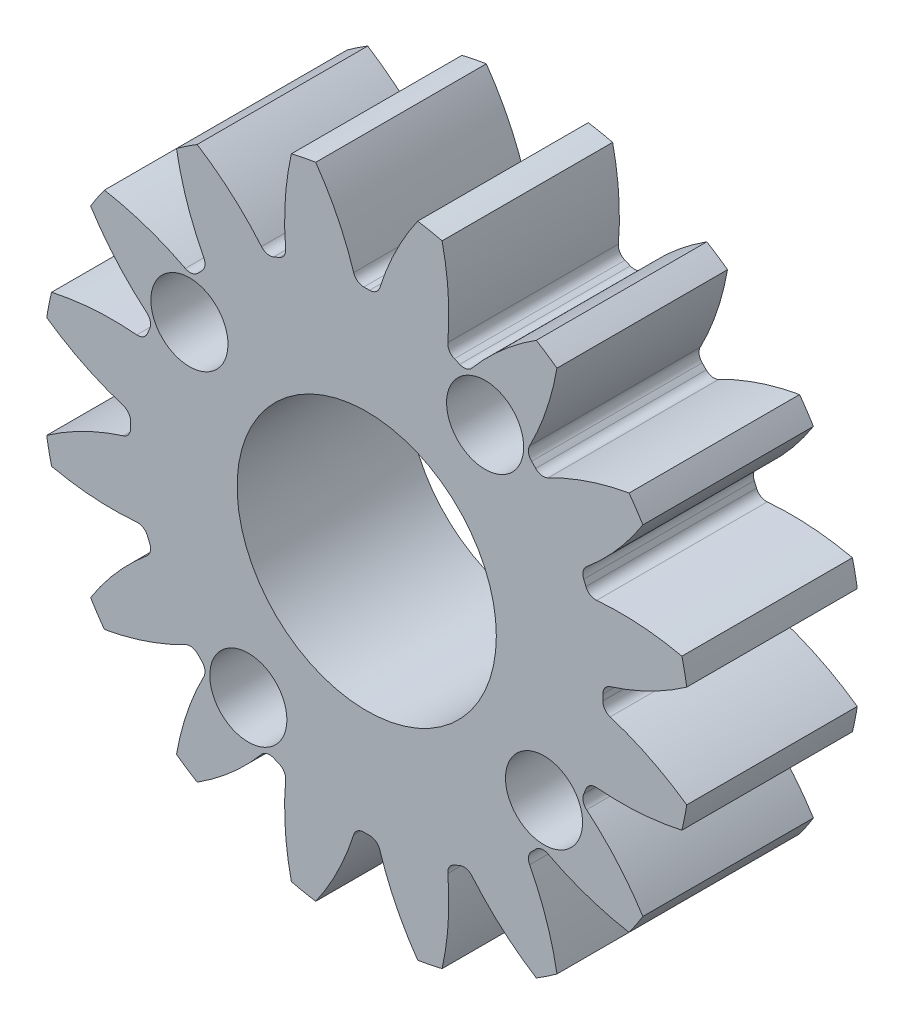
SolidWorks part; units mm, degrees
ref_plane "Front Plane" through (0, 0, 0) normal (0, 0, 1) x (1, 0, 0)
ref_plane "Top Plane" through (0, 0, 0) normal (0, 1, 0) x (1, 0, 0)
ref_plane "Right Plane" through (0, 0, 0) normal (1, 0, 0) x (0, 0, -1)
sketch "Sketch1" plane through (0, 0, 0) normal (0, 0, 1) x (1, 0, 0)
  line L0 (-203.2, 0) -> (203.2, 0) construction
  circle A0 centre (0, 0) radius 12.065 construction
  circle A1 centre (0, 0) radius 10.4775 construction
  circle A2 centre (0, 0) radius 8.7908 construction
  circle A3 centre (0, 0) radius 10.3251 construction
  circle A4 centre (0, 0) radius 6.35 construction
  circle A5 centre (0, 0) radius 10.3187 construction
  dimension "D2" = 1.5875
  dimension "D3" = 3.2742
  dimension "D1" = 3.2742
sketch "Sketch2" plane through (0, 0, 0) normal (1, 0, 0) x (0, 0, -1)
  line L0 (0, 0) -> (-19.05, 0) construction
  line L1 (-19.05, 0) -> (-31.75, 0) construction
  dimension "Overall Width" = 31.75
  dimension "Face Width" = 19.05
sketch "Sketch4" plane through (0, 0, 0) normal (1, 0, 0) x (0, 0, -1)
  line L0 (-31.75, 6.35) -> (-31.75, 10.3251)
  line L1 (-31.75, 10.3251) -> (-19.05, 10.3251)
  line L2 (-19.05, 10.3251) -> (-19.05, 12.065)
  line L3 (-19.05, 12.065) -> (0, 12.065)
  line L4 (0, 12.065) -> (0, 6.35)
  line L5 (-19.05, 10.3251) -> (-19.05, 0) construction
  line L6 (0, 12.065) -> (0, -12.065) construction
  line L7 (-19.05, 10.3251) -> (0, 10.3251) construction
  line L12 (-31.75, 6.35) -> (0, 6.35)
revolve "Revolve1" add sketch "Sketch4" angle 360 about L1
fillet "Fillet2" radius 0.2413 4 edges at (0, 10.3251, 31.75) (0, 10.3251, 19.05) (0, 12.065, 19.05) (0, 12.065, 0)
sketch "Sketch7" plane through (0, 0, 19.05) normal (0, 0, 1) x (1, 0, 0)
  line L0 (0, 0) -> (0, 12.065) construction
  line L1 (1.027, 10.427) -> (1.7513, 11.9372) construction
  line L3 (2.3538, 11.8332) -> (2.0441, 10.2762) construction
  line L4 (2.0441, 10.2762) -> (1.715, 8.6219) construction
  line L5 (0, 0) -> (1.715, 8.6219) construction
  line L6 (1.027, 10.427) -> (0, 0) construction
  line L7 (1.027, 10.427) -> (1.1826, 12.0069) construction
  line L8 (1.027, 10.427) -> (0, 0) construction
  circle A0 centre (0, 0) radius 12.065 construction
  arc A1 (-0.1077, 8.7901) -> (0.1077, 8.7901) centre (0, 0) cw
  circle A2 centre (0, 0) radius 8.7908 construction
  arc A3 (-1.027, 10.427) -> (1.027, 10.427) centre (0, 0) cw construction
  circle A4 centre (0, 0) radius 10.4775 construction
  arc A5 (2.8062, 11.7341) -> (1.8979, 11.9148) centre (0, 0) ccw construction
  arc A6 (1.027, 10.427) -> (3.0415, 10.0263) centre (0, 0) cw construction
  arc A7 (-1.8979, 11.9148) -> (1.8979, 11.9148) centre (0, 0) cw
  arc A8 (0.487, 9.0642) -> (1.8979, 11.9148) centre (10.4739, 5.8957) cw
  arc A9 (-0.487, 9.0642) -> (-1.8979, 11.9148) centre (-10.4739, 5.8957) ccw
  arc A10 (-0.1077, 8.7901) -> (-0.487, 9.0642) centre (-0.1125, 9.183) cw
  arc A11 (0.1077, 8.7901) -> (0.487, 9.0642) centre (0.1125, 9.183) ccw
  point P26 (-0.4017, 8.7816)
  point P29 (0.4017, 8.7816)
  dimension "D4" = 0.3929
  dimension "D5" = 10.4775
  dimension "D3" = 20
  dimension "D1" = 4.1145
  dimension "D2" = 2.0573
extrude "Cut-Extrude2" cut sketch "Sketch7" against normal through all
pattern_circular "CirPattern1" count 16 over 360 about axis through (0, 0, 0) along (0, 0, 1) of "Cut-Extrude2"
sketch "Sketch9" [suppressed] plane through (0, 0, 0) normal (0, 0, 1) x (1, 0, 0)
  circle A0 centre (0, 0) radius 10.3187 construction
  circle A1 centre (0, 0) radius 10.3187
ref_plane "Plane1" through (0, 0, 0) normal (0, 0, -1) x (-1, 0, 0)
ref_plane "Plane2" through (0, 0, 31.75) normal (0, 0, 1) x (1, 0, 0)
sketch "Sketch10" plane through (0, 0, 31.75) normal (0, 0, 1) x (1, 0, 0)
  circle A0 centre (0, 0) radius 29.0934
extrude "Cut-Extrude3" cut sketch "Sketch10" against normal blind 15.24
sketch "Sketch11" plane through (0, 0, 0) normal (0, 0, -1) x (-1, 0, 0)
  circle A0 centre (0, 0) radius 20.5552
extrude "Cut-Extrude4" cut sketch "Sketch11" against normal blind 10.16
sketch "Sketch12" plane through (0, 0, 16.51) normal (0, 0, 1) x (1, 0, 0)
  circle A0 centre (0, 0) radius 7.9171
  circle A1 centre (0, 0) radius 4.826
  dimension "D1" = 9.652
extrude "Boss-Extrude1" add sketch "Sketch12" against normal up to surface (6.35 mm away) up to face at (0, 6.35, 10.16)
sketch "Эскиз1" plane through (0, 0, 0) normal (0, 0, -1) x (-1, 0, 0)
  line L0 (0, 0) -> (17.9765, 12.0041) construction
  circle A0 centre (6.601, 4.408) radius 1.4351
  circle A1 centre (4.408, -6.601) radius 1.4351
  circle A2 centre (-6.601, -4.408) radius 1.4351
  circle A3 centre (-4.408, 6.601) radius 1.4351
  dimension "D3" = 2.8702
  dimension "D2" = 7.9375
  dimension "D1" = 4
extrude "Вырез-Вытянуть1" cut sketch "Эскиз1" against normal through all
sketch "Sketch13" plane through (0, 0, 16.51) normal (0, 0, 1) x (1, 0, 0)
  circle A0 centre (-4.408, -6.601) radius 1.4351 construction
  circle A1 centre (-4.408, -6.601) radius 1.4351
  circle A2 centre (6.601, -4.408) radius 1.4351 construction
  circle A3 centre (4.408, 6.601) radius 1.4351 construction
  circle A4 centre (-6.601, 4.408) radius 1.4351 construction
  circle A5 centre (6.601, -4.408) radius 1.4351
  circle A6 centre (4.408, 6.601) radius 1.4351
  circle A7 centre (-6.601, 4.408) radius 1.4351
  circle A8 centre (0, 0) radius 4.826 construction
  circle A9 centre (0, 0) radius 4.826
  arc A96 (-6.313, -10.2816) -> (-3.9187, -8.1879) centre (-11.9329, -1.4388) ccw
  arc A97 (-3.4633, -8.0798) -> (-3.9187, -8.1879) centre (-3.6181, -8.441) ccw
  arc A98 (-3.4633, -8.0798) -> (-3.2644, -8.1622) centre (0, 0) ccw
  arc A99 (-3.0188, -8.5606) -> (-3.2644, -8.1622) centre (-3.4103, -8.5271) ccw
  arc A100 (-3.0188, -8.5606) -> (-2.8062, -11.7341) centre (7.4205, -9.4552) ccw
  arc A101 (-2.8062, -11.7341) -> (-1.8979, -11.9148) centre (0, 0) ccw
  arc A102 (-1.8979, -11.9148) -> (-0.487, -9.0642) centre (-10.4739, -5.8957) ccw
  arc A103 (-0.1077, -8.7901) -> (-0.487, -9.0642) centre (-0.1125, -9.183) ccw
  arc A104 (-0.1077, -8.7901) -> (0.1077, -8.7901) centre (0, 0) ccw
  arc A105 (0.487, -9.0642) -> (0.1077, -8.7901) centre (0.1125, -9.183) ccw
  arc A106 (0.487, -9.0642) -> (1.8979, -11.9148) centre (10.4739, -5.8957) ccw
  arc A107 (1.8979, -11.9148) -> (2.8062, -11.7341) centre (0, 0) ccw
  arc A108 (2.8062, -11.7341) -> (3.0188, -8.5606) centre (-7.4205, -9.4552) ccw
  arc A109 (3.2644, -8.1622) -> (3.0188, -8.5606) centre (3.4103, -8.5271) ccw
  arc A110 (3.2644, -8.1622) -> (3.4633, -8.0798) centre (0, 0) ccw
  arc A111 (3.9187, -8.1879) -> (3.4633, -8.0798) centre (3.6181, -8.441) ccw
  arc A112 (3.9187, -8.1879) -> (6.313, -10.2816) centre (11.9329, -1.4388) ccw
  arc A113 (6.313, -10.2816) -> (7.083, -9.767) centre (0, 0) ccw
  arc A114 (7.083, -9.767) -> (6.065, -6.7537) centre (-3.2373, -11.5751) ccw
  arc A115 (6.1394, -6.2917) -> (6.065, -6.7537) centre (6.4138, -6.5729) ccw
  arc A116 (6.1394, -6.2917) -> (6.2917, -6.1394) centre (0, 0) ccw
  arc A117 (6.7537, -6.065) -> (6.2917, -6.1394) centre (6.5729, -6.4138) ccw
  arc A118 (6.7537, -6.065) -> (9.767, -7.083) centre (11.5751, 3.2373) ccw
  arc A119 (9.767, -7.083) -> (10.2816, -6.313) centre (0, 0) ccw
  arc A120 (10.2816, -6.313) -> (8.1879, -3.9187) centre (1.4388, -11.9329) ccw
  arc A121 (8.0798, -3.4633) -> (8.1879, -3.9187) centre (8.441, -3.6181) ccw
  arc A122 (8.0798, -3.4633) -> (8.1622, -3.2644) centre (0, 0) ccw
  arc A123 (8.5606, -3.0188) -> (8.1622, -3.2644) centre (8.5271, -3.4103) ccw
  arc A124 (8.5606, -3.0188) -> (11.7341, -2.8062) centre (9.4552, 7.4205) ccw
  arc A125 (11.7341, -2.8062) -> (11.9148, -1.8979) centre (0, 0) ccw
  arc A126 (11.9148, -1.8979) -> (9.0642, -0.487) centre (5.8957, -10.4739) ccw
  arc A127 (8.7901, -0.1077) -> (9.0642, -0.487) centre (9.183, -0.1125) ccw
  arc A128 (8.7901, -0.1077) -> (8.7901, 0.1077) centre (0, 0) ccw
  arc A129 (9.0642, 0.487) -> (8.7901, 0.1077) centre (9.183, 0.1125) ccw
  arc A130 (9.0642, 0.487) -> (11.9148, 1.8979) centre (5.8957, 10.4739) ccw
  arc A131 (11.9148, 1.8979) -> (11.7341, 2.8062) centre (0, 0) ccw
  arc A132 (11.7341, 2.8062) -> (8.5606, 3.0188) centre (9.4552, -7.4205) ccw
  arc A133 (8.1622, 3.2644) -> (8.5606, 3.0188) centre (8.5271, 3.4103) ccw
  arc A134 (8.1622, 3.2644) -> (8.0798, 3.4633) centre (0, 0) ccw
  arc A135 (8.1879, 3.9187) -> (8.0798, 3.4633) centre (8.441, 3.6181) ccw
  arc A136 (8.1879, 3.9187) -> (10.2816, 6.313) centre (1.4388, 11.9329) ccw
  arc A137 (10.2816, 6.313) -> (9.767, 7.083) centre (0, 0) ccw
  arc A138 (9.767, 7.083) -> (6.7537, 6.065) centre (11.5751, -3.2373) ccw
  arc A139 (6.2917, 6.1394) -> (6.7537, 6.065) centre (6.5729, 6.4138) ccw
  arc A140 (6.2917, 6.1394) -> (6.1394, 6.2917) centre (0, 0) ccw
  arc A141 (6.065, 6.7537) -> (6.1394, 6.2917) centre (6.4138, 6.5729) ccw
  arc A142 (6.065, 6.7537) -> (7.083, 9.767) centre (-3.2373, 11.5751) ccw
  arc A143 (7.083, 9.767) -> (6.313, 10.2816) centre (0, 0) ccw
  arc A144 (6.313, 10.2816) -> (3.9187, 8.1879) centre (11.9329, 1.4388) ccw
  arc A145 (3.4633, 8.0798) -> (3.9187, 8.1879) centre (3.6181, 8.441) ccw
  arc A146 (3.4633, 8.0798) -> (3.2644, 8.1622) centre (0, 0) ccw
  arc A147 (3.0188, 8.5606) -> (3.2644, 8.1622) centre (3.4103, 8.5271) ccw
  arc A148 (3.0188, 8.5606) -> (2.8062, 11.7341) centre (-7.4205, 9.4552) ccw
  arc A149 (2.8062, 11.7341) -> (1.8979, 11.9148) centre (0, 0) ccw
  arc A150 (1.8979, 11.9148) -> (0.487, 9.0642) centre (10.4739, 5.8957) ccw
  arc A151 (0.1077, 8.7901) -> (0.487, 9.0642) centre (0.1125, 9.183) ccw
  arc A152 (0.1077, 8.7901) -> (-0.1077, 8.7901) centre (0, 0) ccw
  arc A153 (-0.487, 9.0642) -> (-0.1077, 8.7901) centre (-0.1125, 9.183) ccw
  arc A154 (-0.487, 9.0642) -> (-1.8979, 11.9148) centre (-10.4739, 5.8957) ccw
  arc A155 (-1.8979, 11.9148) -> (-2.8062, 11.7341) centre (0, 0) ccw
  arc A156 (-2.8062, 11.7341) -> (-3.0188, 8.5606) centre (7.4205, 9.4552) ccw
  arc A157 (-3.2644, 8.1622) -> (-3.0188, 8.5606) centre (-3.4103, 8.5271) ccw
  arc A158 (-3.2644, 8.1622) -> (-3.4633, 8.0798) centre (0, 0) ccw
  arc A159 (-3.9187, 8.1879) -> (-3.4633, 8.0798) centre (-3.6181, 8.441) ccw
  arc A160 (-3.9187, 8.1879) -> (-6.313, 10.2816) centre (-11.9329, 1.4388) ccw
  arc A161 (-6.313, 10.2816) -> (-7.083, 9.767) centre (0, 0) ccw
  arc A162 (-7.083, 9.767) -> (-6.065, 6.7537) centre (3.2373, 11.5751) ccw
  arc A163 (-6.1394, 6.2917) -> (-6.065, 6.7537) centre (-6.4138, 6.5729) ccw
  arc A164 (-6.1394, 6.2917) -> (-6.2917, 6.1394) centre (0, 0) ccw
  arc A165 (-6.7537, 6.065) -> (-6.2917, 6.1394) centre (-6.5729, 6.4138) ccw
  arc A166 (-6.7537, 6.065) -> (-9.767, 7.083) centre (-11.5751, -3.2373) ccw
  arc A167 (-9.767, 7.083) -> (-10.2816, 6.313) centre (0, 0) ccw
  arc A168 (-10.2816, 6.313) -> (-8.1879, 3.9187) centre (-1.4388, 11.9329) ccw
  arc A169 (-8.0798, 3.4633) -> (-8.1879, 3.9187) centre (-8.441, 3.6181) ccw
  arc A170 (-8.0798, 3.4633) -> (-8.1622, 3.2644) centre (0, 0) ccw
  arc A171 (-8.5606, 3.0188) -> (-8.1622, 3.2644) centre (-8.5271, 3.4103) ccw
  arc A172 (-8.5606, 3.0188) -> (-11.7341, 2.8062) centre (-9.4552, -7.4205) ccw
  arc A173 (-11.7341, 2.8062) -> (-11.9148, 1.8979) centre (0, 0) ccw
  arc A174 (-11.9148, 1.8979) -> (-9.0642, 0.487) centre (-5.8957, 10.4739) ccw
  arc A175 (-8.7901, 0.1077) -> (-9.0642, 0.487) centre (-9.183, 0.1125) ccw
  arc A176 (-8.7901, 0.1077) -> (-8.7901, -0.1077) centre (0, 0) ccw
  arc A177 (-9.0642, -0.487) -> (-8.7901, -0.1077) centre (-9.183, -0.1125) ccw
  arc A178 (-9.0642, -0.487) -> (-11.9148, -1.8979) centre (-5.8957, -10.4739) ccw
  arc A179 (-11.9148, -1.8979) -> (-11.7341, -2.8062) centre (0, 0) ccw
  arc A180 (-11.7341, -2.8062) -> (-8.5606, -3.0188) centre (-9.4552, 7.4205) ccw
  arc A181 (-8.1622, -3.2644) -> (-8.5606, -3.0188) centre (-8.5271, -3.4103) ccw
  arc A182 (-8.1622, -3.2644) -> (-8.0798, -3.4633) centre (0, 0) ccw
  arc A183 (-8.1879, -3.9187) -> (-8.0798, -3.4633) centre (-8.441, -3.6181) ccw
  arc A184 (-8.1879, -3.9187) -> (-10.2816, -6.313) centre (-1.4388, -11.9329) ccw
  arc A185 (-10.2816, -6.313) -> (-9.767, -7.083) centre (0, 0) ccw
  arc A186 (-9.767, -7.083) -> (-6.7537, -6.065) centre (-11.5751, 3.2373) ccw
  arc A187 (-6.2917, -6.1394) -> (-6.7537, -6.065) centre (-6.5729, -6.4138) ccw
  arc A188 (-6.2917, -6.1394) -> (-6.1394, -6.2917) centre (0, 0) ccw
  arc A189 (-6.065, -6.7537) -> (-6.1394, -6.2917) centre (-6.4138, -6.5729) ccw
  arc A190 (-6.065, -6.7537) -> (-7.083, -9.767) centre (3.2373, -11.5751) ccw
  arc A191 (-7.083, -9.767) -> (-6.313, -10.2816) centre (0, 0) ccw
  arc A192 (-6.313, -10.2816) -> (-3.9187, -8.1879) centre (-11.9329, -1.4388) ccw
  arc A193 (-3.4633, -8.0798) -> (-3.9187, -8.1879) centre (-3.6181, -8.441) ccw
  arc A194 (-3.4633, -8.0798) -> (-3.2644, -8.1622) centre (0, 0) ccw
  arc A195 (-3.0188, -8.5606) -> (-3.2644, -8.1622) centre (-3.4103, -8.5271) ccw
  arc A196 (-3.0188, -8.5606) -> (-2.8062, -11.7341) centre (7.4205, -9.4552) ccw
  arc A197 (-2.8062, -11.7341) -> (-1.8979, -11.9148) centre (0, 0) ccw
  arc A198 (-1.8979, -11.9148) -> (-0.487, -9.0642) centre (-10.4739, -5.8957) ccw
  arc A199 (-0.1077, -8.7901) -> (-0.487, -9.0642) centre (-0.1125, -9.183) ccw
  arc A200 (-0.1077, -8.7901) -> (0.1077, -8.7901) centre (0, 0) ccw
  arc A201 (0.487, -9.0642) -> (0.1077, -8.7901) centre (0.1125, -9.183) ccw
  arc A202 (0.487, -9.0642) -> (1.8979, -11.9148) centre (10.4739, -5.8957) ccw
  arc A203 (1.8979, -11.9148) -> (2.8062, -11.7341) centre (0, 0) ccw
  arc A204 (2.8062, -11.7341) -> (3.0188, -8.5606) centre (-7.4205, -9.4552) ccw
  arc A205 (3.2644, -8.1622) -> (3.0188, -8.5606) centre (3.4103, -8.5271) ccw
  arc A206 (3.2644, -8.1622) -> (3.4633, -8.0798) centre (0, 0) ccw
  arc A207 (3.9187, -8.1879) -> (3.4633, -8.0798) centre (3.6181, -8.441) ccw
  arc A208 (3.9187, -8.1879) -> (6.313, -10.2816) centre (11.9329, -1.4388) ccw
  arc A209 (6.313, -10.2816) -> (7.083, -9.767) centre (0, 0) ccw
  arc A210 (7.083, -9.767) -> (6.065, -6.7537) centre (-3.2373, -11.5751) ccw
  arc A211 (6.1394, -6.2917) -> (6.065, -6.7537) centre (6.4138, -6.5729) ccw
  arc A212 (6.1394, -6.2917) -> (6.2917, -6.1394) centre (0, 0) ccw
  arc A213 (6.7537, -6.065) -> (6.2917, -6.1394) centre (6.5729, -6.4138) ccw
  arc A214 (6.7537, -6.065) -> (9.767, -7.083) centre (11.5751, 3.2373) ccw
  arc A215 (9.767, -7.083) -> (10.2816, -6.313) centre (0, 0) ccw
  arc A216 (10.2816, -6.313) -> (8.1879, -3.9187) centre (1.4388, -11.9329) ccw
  arc A217 (8.0798, -3.4633) -> (8.1879, -3.9187) centre (8.441, -3.6181) ccw
  arc A218 (8.0798, -3.4633) -> (8.1622, -3.2644) centre (0, 0) ccw
  arc A219 (8.5606, -3.0188) -> (8.1622, -3.2644) centre (8.5271, -3.4103) ccw
  arc A220 (8.5606, -3.0188) -> (11.7341, -2.8062) centre (9.4552, 7.4205) ccw
  arc A221 (11.7341, -2.8062) -> (11.9148, -1.8979) centre (0, 0) ccw
  arc A222 (11.9148, -1.8979) -> (9.0642, -0.487) centre (5.8957, -10.4739) ccw
  arc A223 (8.7901, -0.1077) -> (9.0642, -0.487) centre (9.183, -0.1125) ccw
  arc A224 (8.7901, -0.1077) -> (8.7901, 0.1077) centre (0, 0) ccw
  arc A225 (9.0642, 0.487) -> (8.7901, 0.1077) centre (9.183, 0.1125) ccw
  arc A226 (9.0642, 0.487) -> (11.9148, 1.8979) centre (5.8957, 10.4739) ccw
  arc A227 (11.9148, 1.8979) -> (11.7341, 2.8062) centre (0, 0) ccw
  arc A228 (11.7341, 2.8062) -> (8.5606, 3.0188) centre (9.4552, -7.4205) ccw
  arc A229 (8.1622, 3.2644) -> (8.5606, 3.0188) centre (8.5271, 3.4103) ccw
  arc A230 (8.1622, 3.2644) -> (8.0798, 3.4633) centre (0, 0) ccw
  arc A231 (8.1879, 3.9187) -> (8.0798, 3.4633) centre (8.441, 3.6181) ccw
  arc A232 (8.1879, 3.9187) -> (10.2816, 6.313) centre (1.4388, 11.9329) ccw
  arc A233 (10.2816, 6.313) -> (9.767, 7.083) centre (0, 0) ccw
  arc A234 (9.767, 7.083) -> (6.7537, 6.065) centre (11.5751, -3.2373) ccw
  arc A235 (6.2917, 6.1394) -> (6.7537, 6.065) centre (6.5729, 6.4138) ccw
  arc A236 (6.2917, 6.1394) -> (6.1394, 6.2917) centre (0, 0) ccw
  arc A237 (6.065, 6.7537) -> (6.1394, 6.2917) centre (6.4138, 6.5729) ccw
  arc A238 (6.065, 6.7537) -> (7.083, 9.767) centre (-3.2373, 11.5751) ccw
  arc A239 (7.083, 9.767) -> (6.313, 10.2816) centre (0, 0) ccw
  arc A240 (6.313, 10.2816) -> (3.9187, 8.1879) centre (11.9329, 1.4388) ccw
  arc A241 (3.4633, 8.0798) -> (3.9187, 8.1879) centre (3.6181, 8.441) ccw
  arc A242 (3.4633, 8.0798) -> (3.2644, 8.1622) centre (0, 0) ccw
  arc A243 (3.0188, 8.5606) -> (3.2644, 8.1622) centre (3.4103, 8.5271) ccw
  arc A244 (3.0188, 8.5606) -> (2.8062, 11.7341) centre (-7.4205, 9.4552) ccw
  arc A245 (2.8062, 11.7341) -> (1.8979, 11.9148) centre (0, 0) ccw
  arc A246 (1.8979, 11.9148) -> (0.487, 9.0642) centre (10.4739, 5.8957) ccw
  arc A247 (0.1077, 8.7901) -> (0.487, 9.0642) centre (0.1125, 9.183) ccw
  arc A248 (0.1077, 8.7901) -> (-0.1077, 8.7901) centre (0, 0) ccw
  arc A249 (-0.487, 9.0642) -> (-0.1077, 8.7901) centre (-0.1125, 9.183) ccw
  arc A250 (-0.487, 9.0642) -> (-1.8979, 11.9148) centre (-10.4739, 5.8957) ccw
  arc A251 (-1.8979, 11.9148) -> (-2.8062, 11.7341) centre (0, 0) ccw
  arc A252 (-2.8062, 11.7341) -> (-3.0188, 8.5606) centre (7.4205, 9.4552) ccw
  arc A253 (-3.2644, 8.1622) -> (-3.0188, 8.5606) centre (-3.4103, 8.5271) ccw
  arc A254 (-3.2644, 8.1622) -> (-3.4633, 8.0798) centre (0, 0) ccw
  arc A255 (-3.9187, 8.1879) -> (-3.4633, 8.0798) centre (-3.6181, 8.441) ccw
  arc A256 (-3.9187, 8.1879) -> (-6.313, 10.2816) centre (-11.9329, 1.4388) ccw
  arc A257 (-6.313, 10.2816) -> (-7.083, 9.767) centre (0, 0) ccw
  arc A258 (-7.083, 9.767) -> (-6.065, 6.7537) centre (3.2373, 11.5751) ccw
  arc A259 (-6.1394, 6.2917) -> (-6.065, 6.7537) centre (-6.4138, 6.5729) ccw
  arc A260 (-6.1394, 6.2917) -> (-6.2917, 6.1394) centre (0, 0) ccw
  arc A261 (-6.7537, 6.065) -> (-6.2917, 6.1394) centre (-6.5729, 6.4138) ccw
  arc A262 (-6.7537, 6.065) -> (-9.767, 7.083) centre (-11.5751, -3.2373) ccw
  arc A263 (-9.767, 7.083) -> (-10.2816, 6.313) centre (0, 0) ccw
  arc A264 (-10.2816, 6.313) -> (-8.1879, 3.9187) centre (-1.4388, 11.9329) ccw
  arc A265 (-8.0798, 3.4633) -> (-8.1879, 3.9187) centre (-8.441, 3.6181) ccw
  arc A266 (-8.0798, 3.4633) -> (-8.1622, 3.2644) centre (0, 0) ccw
  arc A267 (-8.5606, 3.0188) -> (-8.1622, 3.2644) centre (-8.5271, 3.4103) ccw
  arc A268 (-8.5606, 3.0188) -> (-11.7341, 2.8062) centre (-9.4552, -7.4205) ccw
  arc A269 (-11.7341, 2.8062) -> (-11.9148, 1.8979) centre (0, 0) ccw
  arc A270 (-11.9148, 1.8979) -> (-9.0642, 0.487) centre (-5.8957, 10.4739) ccw
  arc A271 (-8.7901, 0.1077) -> (-9.0642, 0.487) centre (-9.183, 0.1125) ccw
  arc A272 (-8.7901, 0.1077) -> (-8.7901, -0.1077) centre (0, 0) ccw
  arc A273 (-9.0642, -0.487) -> (-8.7901, -0.1077) centre (-9.183, -0.1125) ccw
  arc A274 (-9.0642, -0.487) -> (-11.9148, -1.8979) centre (-5.8957, -10.4739) ccw
  arc A275 (-11.9148, -1.8979) -> (-11.7341, -2.8062) centre (0, 0) ccw
  arc A276 (-11.7341, -2.8062) -> (-8.5606, -3.0188) centre (-9.4552, 7.4205) ccw
  arc A277 (-8.1622, -3.2644) -> (-8.5606, -3.0188) centre (-8.5271, -3.4103) ccw
  arc A278 (-8.1622, -3.2644) -> (-8.0798, -3.4633) centre (0, 0) ccw
  arc A279 (-8.1879, -3.9187) -> (-8.0798, -3.4633) centre (-8.441, -3.6181) ccw
  arc A280 (-8.1879, -3.9187) -> (-10.2816, -6.313) centre (-1.4388, -11.9329) ccw
  arc A281 (-10.2816, -6.313) -> (-9.767, -7.083) centre (0, 0) ccw
  arc A282 (-9.767, -7.083) -> (-6.7537, -6.065) centre (-11.5751, 3.2373) ccw
  arc A283 (-6.2917, -6.1394) -> (-6.7537, -6.065) centre (-6.5729, -6.4138) ccw
  arc A284 (-6.2917, -6.1394) -> (-6.1394, -6.2917) centre (0, 0) ccw
  arc A285 (-6.065, -6.7537) -> (-6.1394, -6.2917) centre (-6.4138, -6.5729) ccw
  arc A286 (-6.065, -6.7537) -> (-7.083, -9.767) centre (3.2373, -11.5751) ccw
  arc A287 (-7.083, -9.767) -> (-6.313, -10.2816) centre (0, 0) ccw
  dimension "D1" = 0
equation "\"D1@Sketch1\"=2.5*(\"Pitch Dia.@Sketch1\"/\"Number of Teeth@Sketch1\")"
equation "\"D1@CirPattern1\"=\"Number of Teeth@Sketch1\""
equation "\"D1@Fillet2\"=\"OD@Sketch1\"*.01"
equation "\"D1@Sketch7\"=3.14159*(\"Pitch Dia.@Sketch1\"/\"Number of Teeth@Sketch1\")"
equation "\"D2@Sketch7\"=\"D1@Sketch7\"/2"
equation "\"D4@Sketch7\"=\"D1@Sketch7\"*.0955"
equation "\"D5@Sketch7\"=\"Pitch Dia.@Sketch1\"/2"
